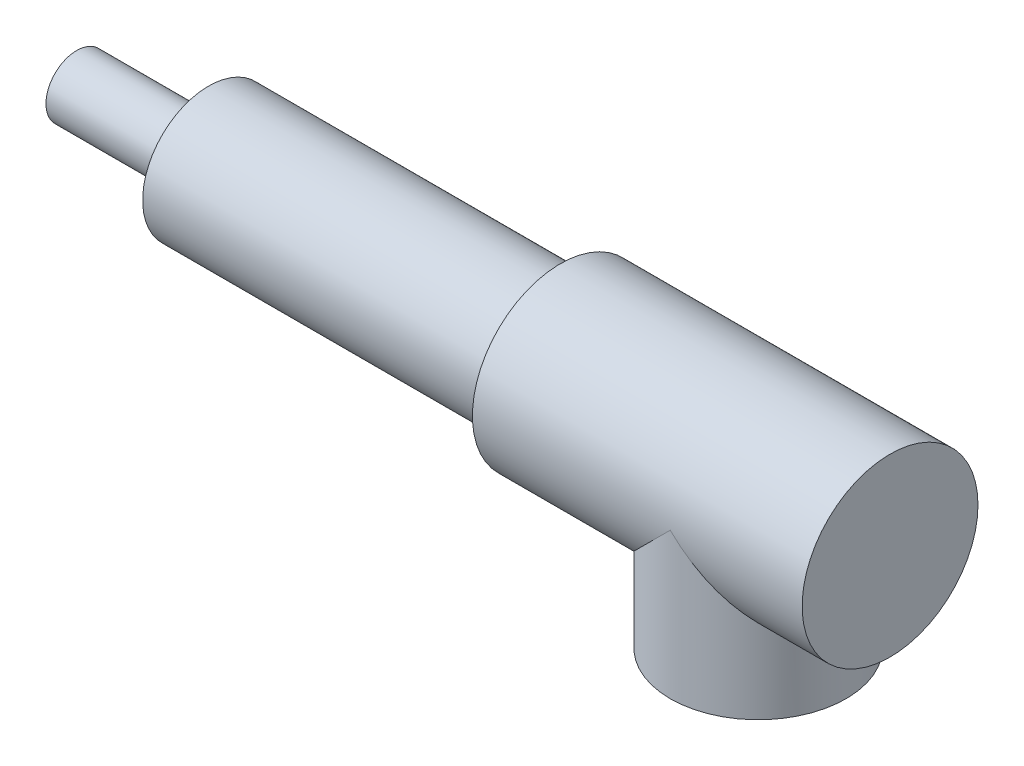
SolidWorks part; units mm, degrees
ref_plane "Front Plane" through (0, 0, 0) normal (0, 0, 1) x (1, 0, 0)
ref_plane "Top Plane" through (0, 0, 0) normal (0, 1, 0) x (1, 0, 0)
ref_plane "Right Plane" through (0, 0, 0) normal (1, 0, 0) x (0, 0, -1)
sketch "Sketch1" plane through (0, 0, 0) normal (0, 0, 1) x (1, 0, 0)
  line L0 (0, 0) -> (75, 0)
  dimension "D1" = 75
sketch "Sketch2" plane through (0, 0, 0) normal (1, 0, 0) x (0, 0, -1)
  circle A0 centre (0, 0) radius 20
  dimension "D1" = 40
sweep "Sweep1" add profiles "Sketch2" path "Sketch1"
sketch "Sketch4" plane through (0, 0, 0) normal (0, 1, 0) x (1, 0, 0)
  line L0 (0, 0) -> (75, 0) construction
  line L1 (75, -20) -> (75, 20) construction
  line L2 (75, 20) -> (0, 20) construction
  circle A0 centre (45, 0) radius 20
  dimension "D1" = 45
extrude "Boss-Extrude1" add sketch "Sketch4" against normal blind 33.2
sketch "Sketch5" plane through (0, 0, 0) normal (0, 1, 0) x (1, 0, 0)
  line L0 (0, 0) -> (-110, 0)
  line L1 (-110, 0) -> (-110, 7)
  line L2 (-110, 7) -> (-80, 7)
  line L3 (-80, 7) -> (-80, 15)
  line L4 (-80, 15) -> (0, 15)
  line L5 (0, 20) -> (0, -20) construction
  line L6 (0, 15) -> (0, 0)
  line L7 (-110, 0) -> (-138.4753, 0) construction
  dimension "D1" = 14
  dimension "D2" = 30
  dimension "D3" = 110
  dimension "D4" = 30
revolve "Revolve1" add sketch "Sketch5" angle 360 about L7
